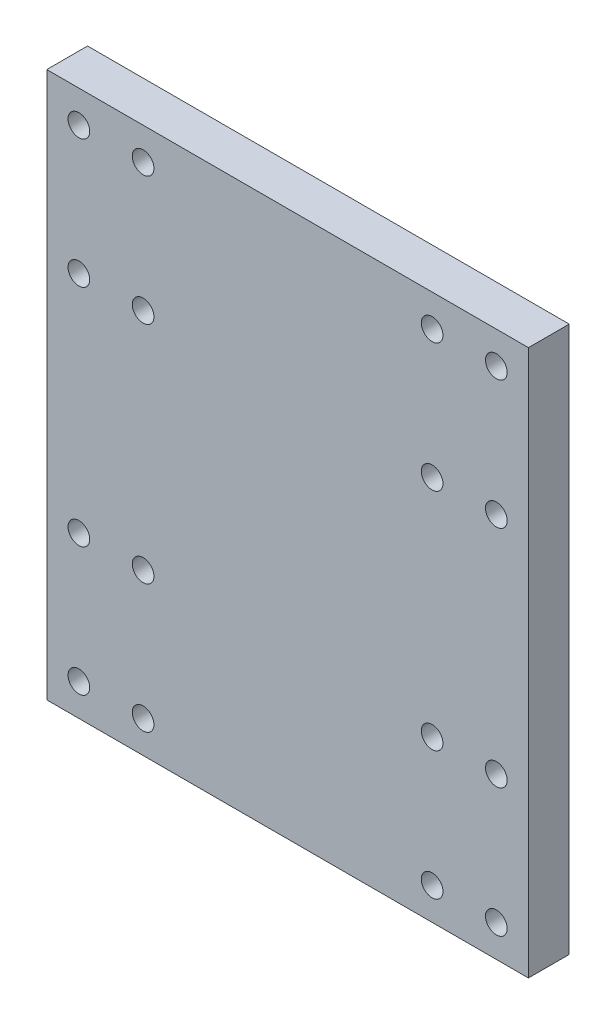
SolidWorks part; units mm, degrees
ref_plane "Alzado" through (0, 0, 0) normal (0, 0, 1) x (1, 0, 0)
ref_plane "Planta" through (0, 0, 0) normal (0, 1, 0) x (1, 0, 0)
ref_plane "Vista lateral" through (0, 0, 0) normal (1, 0, 0) x (0, 0, -1)
sketch "Croquis1" plane through (0, 0, 0) normal (0, 0, 1) x (1, 0, 0)
  line L1 (75, 85) -> (-75, 85)
  line L2 (75, 85) -> (75, -85)
  line L3 (75, -85) -> (-75, -85)
  line L4 (-75, 85) -> (-75, -85)
  line L5 (75, 85) -> (-75, -85) construction
  line L6 (75, -85) -> (-75, 85) construction
  point P0 (0, 0)
  dimension "D1" = 170
  dimension "D2" = 150
extrude "Saliente-Extruir1" add sketch "Croquis1" along normal mid plane 12.7
hole_wizard "Taladro de margen para 1/41" positions "Croquis2" profile "Croquis3" hole size "1/4" standard "Ansi Inch" end condition through all
sketch "Croquis2" plane through (0, 0, 6.35) normal (0, 0, 1) x (1, 0, 0)
  line L0 (0, 0) -> (-50000, 0) construction
  line L1 (0, 0) -> (0, 50000) construction
  point P4 (65, 75)
  point P7 (65, 35)
  point P10 (45, 35)
  point P13 (45, 75)
  point P21 (45, -75)
  point P22 (45, -35)
  point P23 (65, -35)
  point P24 (65, -75)
  point P37 (-65, -75)
  point P38 (-65, -35)
  point P39 (-45, -35)
  point P40 (-45, -75)
  point P41 (-45, 75)
  point P42 (-45, 35)
  point P43 (-65, 35)
  point P44 (-65, 75)
sketch "Croquis3" plane through (65, 75, 6.35) normal (1, 0, 0) x (0, -1, 0)
  line L0 (0, 0) -> (0, 12.7)
  line L1 (0, 12.7) -> (3.3782, 12.7)
  line L2 (3.3782, 12.7) -> (3.3782, 0)
  line L5 (3.3782, 0) -> (0, 0)
  line L11 (0, -6.35) -> (0, 107.95) construction
  dimension "Diámetro de taladro hasta el siguiente" = 6.7564
  dimension "Profundidad de taladro hasta el siguiente" = 12.7
